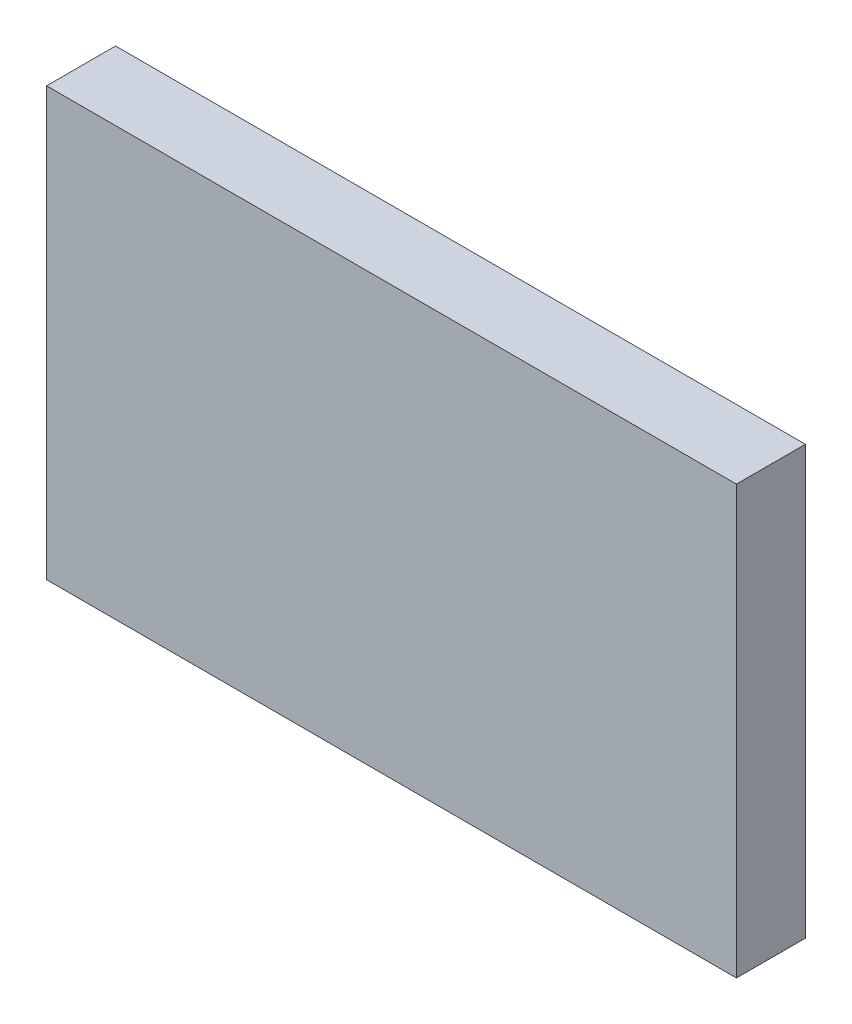
SolidWorks part; units mm, degrees
ref_plane "Front Plane" through (0, 0, 0) normal (0, 0, 1) x (1, 0, 0)
ref_plane "Top Plane" through (0, 0, 0) normal (0, 1, 0) x (1, 0, 0)
ref_plane "Right Plane" through (0, 0, 0) normal (1, 0, 0) x (0, 0, -1)
sketch "Sketch1" plane through (0, 0, 0) normal (0, 0, 1) x (1, 0, 0)
  line L1 (0, 0) -> (63.5, 0)
  line L2 (0, 0) -> (0, 39.37)
  line L3 (0, 39.37) -> (63.5, 39.37)
  line L4 (63.5, 0) -> (63.5, 39.37)
  dimension "D1" = 39.37
  dimension "D2" = 63.5
extrude "Boss-Extrude1" add sketch "Sketch1" against normal blind 6.35
